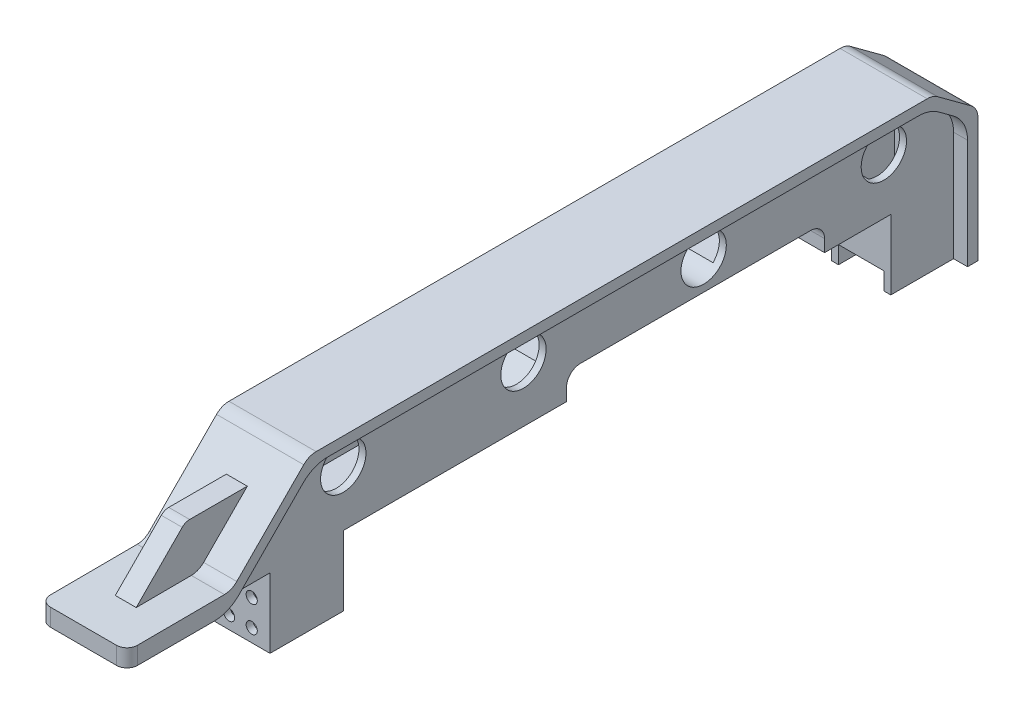
SolidWorks part; units mm, degrees
ref_plane "Front Plane" through (0, 0, 0) normal (0, 0, 1) x (1, 0, 0)
ref_plane "Top Plane" through (0, 0, 0) normal (0, 1, 0) x (1, 0, 0)
ref_plane "Right Plane" through (0, 0, 0) normal (1, 0, 0) x (0, 0, -1)
sketch "Sketch1" plane through (0, 0, 0) normal (1, 0, 0) x (0, 0, -1)
  line L0 (0, 0) -> (-130, 0)
  line L1 (0, 0) -> (74, 0) construction
  line L2 (0, 0) -> (0, 7.5)
  line L3 (0, 7.5) -> (74, 7.5)
  line L4 (74, 7.5) -> (74, 0)
  line L5 (74, 0) -> (114, 0)
  line L6 (-130, 0) -> (-130, 5)
  line L7 (-130, 5) -> (-100.0004, 5.1483)
  line L8 (-100.0004, 5.1483) -> (-77.8685, 27.5)
  line L9 (114, 0) -> (114, 18)
  line L10 (114, 18) -> (101.0882, 27.5)
  line L11 (101.0882, 27.5) -> (-77.8685, 27.5)
  dimension "D1" = 130
  dimension "D2" = 74
  dimension "D3" = 7.5
  dimension "D4" = 40
  dimension "D5" = 30
  dimension "D6" = 5
  dimension "D7" = 135
  dimension "D8" = 20
  dimension "D9" = 18
extrude "Boss-Extrude1" add sketch "Sketch1" along normal blind 25
sketch "Sketch4" plane through (25, 0, 0) normal (1, 0, 0) x (0, 0, -1)
  line L11 (-130, 0) -> (0, 0) construction
  line L12 (-130, 0) -> (0, 0) construction
  line L13 (-100.8762, 0) -> (0, 0)
  line L14 (0, 0) -> (111, 0)
  line L15 (74, 0) -> (114, 0) construction
  line L16 (111, 0) -> (111, 3)
  line L22 (-3, 3) -> (-3, 10.5)
  line L23 (-3, 10.5) -> (77, 10.5)
  line L24 (77, 10.5) -> (77, 3)
  line L25 (77, 3) -> (111, 3)
  line L26 (111, 3) -> (111, 16.4828)
  line L27 (111, 16.4828) -> (100.1035, 24.5)
  line L28 (100.1035, 24.5) -> (-76.6172, 24.5)
  line L29 (-76.6172, 24.5) -> (-97.9057, 3)
  line L30 (-97.9057, 3) -> (-3, 3)
  line L35 (111, 3) -> (111, 16.4828)
  line L36 (111, 16.4828) -> (100.1035, 24.5)
  line L37 (100.1035, 24.5) -> (-76.6172, 24.5)
  line L38 (-76.6172, 24.5) -> (-100.8762, 0)
  dimension "D1" = 3
extrude "Cut-Extrude1" cut sketch "Sketch4" against normal blind 4
ref_plane "Plane1" through (12.5, 0, 0) normal (1, 0, 0) x (0, 0, -1)
mirror "Mirror2" about plane through (12.5, 0, 0) normal (1, 0, 0) of "Cut-Extrude1"
fillet "Fillet1" radius 4 2 edges at (12.5, 7.5, -74) (12.5, 7.5, 0)
fillet "Fillet2" radius 10 8 edges at (23, 16.4828, -111) (23, 24.5, -100.1035) (2, 16.4828, -111) (2, 24.5, -100.1035) (2, 24.5, 76.6172) (23, 24.5, 76.6172) (2, 0, 100.8762) (23, 0, 100.8762)
fillet "Fillet3" radius 5 4 edges at (12.5, 18, -114) (12.5, 27.5, -101.0882) (12.5, 27.5, 77.8685) (12.5, 5.1483, 100.0004)
fillet "Fillet4" radius 3 2 edges at (0, 2.5, 130) (25, 2.5, 130)
sketch "Sketch5" plane through (12.5, 0, 0) normal (1, 0, 0) x (0, 0, -1)
  line L0 (-117.866, 5.06) -> (-103.7939, 19.2718)
  line L1 (-102.0714, 5.138) -> (-127, 5.0148) construction
  line L2 (-79.3359, 26.018) -> (-98.5432, 6.62) construction
  line L3 (-103.7939, 19.2718) -> (-72.6053, 19.2718)
  line L4 (-117.866, 5.06) -> (-95.866, 5.06)
  line L5 (-79.552, 21.536) -> (-97.9414, 2.964) construction
  line L6 (-72.6053, 19.2718) -> (-95.866, 5.06)
  dimension "D1" = 22
  dimension "D2" = 20
extrude "Boss-Extrude2" add sketch "Sketch5" along normal blind 3 and the other way blind 3
fillet "Fillet5" radius 3 1 edges at (12.5, 19.2718, 103.7939)
sketch "Sketch6" plane through (0, 0, 0) normal (0, -1, 0) x (1, 0, 0)
  line L1 (0, -111) -> (0, -114) construction
  line L2 (0, -111) -> (4, -111)
  line L3 (0, -111) -> (0, -114)
  line L4 (0, -114) -> (25, -114)
  line L5 (25, -111) -> (25, -114)
  line L6 (0, -111) -> (25, -114) construction
  line L7 (0, -114) -> (25, -111) construction
  line L8 (4, -111) -> (0, -111) construction
  line L9 (25, -114) -> (0, -114) construction
  line L10 (4, -74) -> (4, -111) construction
  line L11 (4, -111) -> (21, -111) construction
  line L12 (4, -111) -> (4, -93)
  line L13 (4, -93) -> (21, -93)
  line L14 (21, -111) -> (21, -93)
  line L15 (4, -111) -> (21, -93) construction
  line L16 (4, -93) -> (21, -111) construction
  line L17 (21, -74) -> (21, -111) construction
  line L18 (4, -111) -> (21, -111) construction
  line L19 (21, -111) -> (25, -111)
  line L21 (19, -95) -> (6, -95)
  line L22 (19, -95) -> (19, -109)
  line L23 (19, -109) -> (6, -109)
  line L24 (6, -95) -> (6, -109)
  line L25 (19, -95) -> (6, -109) construction
  line L26 (19, -109) -> (6, -95) construction
  point P6 (12.5, -112.5)
  point P16 (12.5, -102)
  point P21 (12.5, -102)
  dimension "D1" = 18
  dimension "D2" = 2
  dimension "D3" = 2
extrude "Boss-Extrude3" add sketch "Sketch6" along normal blind 20
sketch "Sketch7" plane through (0, -20, 0) normal (0, -1, 0) x (1, 0, 0)
  line L0 (19, -109) -> (19, -95) construction
  line L1 (19, -95) -> (6, -95)
  line L2 (19, -95) -> (19, -93)
  line L3 (19, -93) -> (6, -93)
  line L4 (6, -95) -> (6, -93)
  line L5 (19, -95) -> (6, -93) construction
  line L6 (19, -93) -> (6, -95) construction
  line L7 (19, -95) -> (6, -95) construction
  line L8 (21, -93) -> (4, -93) construction
  line L9 (6, -95) -> (6, -109) construction
  point P4 (12.5, -94)
sketch "Sketch8" plane through (0, 0, 0) normal (0, -1, 0) x (1, 0, 0)
  line L5 (21, 85) -> (21, 130) construction
  line L6 (21, 105.0473) -> (21, 0) construction
  line L8 (22, 130) -> (3, 130) construction
  line L9 (4, 105.0473) -> (4, 0) construction
  line L10 (21, 85) -> (4, 85)
  line L11 (21, 85) -> (21, 64)
  line L12 (21, 64) -> (19, 64)
  line L13 (4, 85) -> (4, 64)
  line L14 (21, 85) -> (4, 64) construction
  line L15 (21, 64) -> (4, 85) construction
  line L16 (19, 64) -> (6, 64) construction
  line L17 (6, 64) -> (19, 64) construction
  line L18 (6, 64) -> (6, 83)
  line L19 (6, 83) -> (19, 83)
  line L20 (19, 64) -> (19, 83)
  line L21 (6, 64) -> (19, 83) construction
  line L22 (6, 83) -> (19, 64) construction
  line L23 (6, 64) -> (4, 64)
  point P9 (12.5, 74.5)
  point P16 (12.5, 73.5)
  dimension "D1" = 45
  dimension "D2" = 21
  dimension "D3" = 2
  dimension "D4" = 2
  dimension "D5" = 2
extrude "Boss-Extrude4" add sketch "Sketch8" along normal blind 20
sketch "Sketch9" plane through (0, 0, 0) normal (0, -1, 0) x (1, 0, 0)
  line L0 (6, 64) -> (6, 83) construction
  line L1 (6, 64) -> (19, 64)
  line L2 (6, 64) -> (6, 66)
  line L3 (6, 66) -> (19, 66)
  line L4 (19, 64) -> (19, 66)
  line L5 (6, 64) -> (19, 66) construction
  line L6 (6, 66) -> (19, 64) construction
  line L7 (19, 83) -> (19, 64) construction
  point P4 (12.5, 65)
  dimension "D1" = 2
extrude "Boss-Extrude5" add sketch "Sketch9" along normal blind 8
extrude "Cut-Extrude2" cut sketch "Sketch7" against normal blind 5 contours L3 L4 L1 L2
sketch "Sketch11" plane through (0, 0, -114) normal (0, 0, -1) x (-1, 0, 0)
  line L0 (0, -20) -> (0, -12.5) construction
  line L1 (0, -20) -> (-25, -20) construction
  line L2 (0, -20) -> (0, 15.4713) construction
  line L3 (0, -16.25) -> (-25, -16.25) construction
  line L4 (-25, -20) -> (-25, 15.4713) construction
  line L5 (0, -16.25) -> (-9.25, -16.25) construction
  line L6 (-12.5, -20) -> (-12.5, -5) construction
  line L7 (0, -20) -> (0, -16.25)
  line L8 (-25, -20) -> (-25, -12.5) construction
  line L9 (-25, -12.5) -> (0, -12.5) construction
  circle A0 centre (-9.25, -16.25) radius 1.6
  circle A1 centre (-15.75, -16.25) radius 1.6
  circle A2 centre (-15.75, -8.75) radius 1.6
  circle A3 centre (-9.25, -8.75) radius 1.6
  circle A4 centre (-15.75, -16.25) radius 3 construction
  dimension "D2" = 3.2
  dimension "D5" = 6
  dimension "D1" = 9.25
  dimension "D3" = 3.75
  dimension "D4" = 7.5
extrude "Cut-Extrude3" cut sketch "Sketch11" against normal up to surface (19 mm away) contours A1 | A2 | A3 | A0 up to face at (12.5, -7.5, -95)
sketch "Sketch12" plane through (0, 0, 85) normal (0, 0, 1) x (1, 0, 0)
  line L0 (15.75, -8.75) -> (21, -8.75) construction
  line L1 (15.75, -8.75) -> (15.75, -5) construction
  line L3 (12.5, -20) -> (12.5, -5) construction
  line L6 (0, -12.5) -> (25, -12.5) construction
  line L7 (4, -20) -> (21, -20) construction
  line L8 (4, -20) -> (4, 0) construction
  line L9 (21, -20) -> (21, 0) construction
  circle A0 centre (15.75, -16.25) radius 1.6
  circle A1 centre (9.25, -16.25) radius 1.6
  circle A2 centre (9.25, -8.75) radius 1.6
  circle A3 centre (15.75, -8.75) radius 1.6
  circle A4 centre (9.25, -16.25) radius 3 construction
  dimension "D1" = 3.2
  dimension "D2" = 5.25
  dimension "D3" = 3.75
extrude "Cut-Extrude4" cut sketch "Sketch12" against normal up to surface (2 mm away) up to face at (12.5, -10, 83)
sketch "Sketch14" plane through (12.5, 0, 0) normal (1, 0, 0) x (0, 0, -1)
  line L0 (-83, 0) -> (-83, 13.4752)
  line L1 (-66, 0) -> (-66, 4)
  line L2 (-66, 4) -> (-13.3251, 4)
  line L3 (-13.3251, 4) -> (-5.8251, 11.5)
  line L4 (-5.8251, 11.5) -> (87.0794, 11.5)
  line L5 (95, 0) -> (95, 3.5794)
  line L6 (95, 3.5794) -> (87.0794, 11.5)
  line L7 (109, 0) -> (109, 10.0924)
  line L8 (109, -20) -> (109, 0) construction
  line L9 (95, 0) -> (109, 0) construction
  line L10 (109, 10.0924) -> (95.5924, 23.5)
  line L15 (-72.9752, 23.5) -> (-83, 13.4752)
  line L16 (-83, 0) -> (-66, 0)
  line L17 (95, 0) -> (109, 0)
  line L18 (95.5924, 23.5) -> (-72.9752, 23.5)
  line L19 (-64, 0) -> (0, 0) construction
  line L20 (99.447, 27.5) -> (-75.783, 27.5) construction
  line L21 (70, 7.5) -> (4, 7.5) construction
  dimension "D1" = 135
  dimension "D2" = 135
  dimension "D3" = 135
  dimension "D4" = 135
  dimension "D5" = 4
  dimension "D6" = 4
  dimension "D7" = 4
extrude "Cut-Extrude5" cut sketch "Sketch14" against normal blind 6.5 and the other way blind 6.5
sketch "Sketch15" plane through (4, 0, 0) normal (-1, 0, 0) x (0, 0, 1)
  line L0 (-37, 7.5) -> (-37, 24.5) construction
  line L1 (-70, 7.5) -> (-4, 7.5) construction
  line L2 (-96.8211, 24.5) -> (72.4461, 24.5) construction
  line L3 (-37, 16) -> (-111, 16) construction
  line L4 (-37, 16) -> (84, 16) construction
  line L6 (-111, 16) -> (-13.5, 16) construction
  line L7 (-13.5, 16) -> (-13.5, 7.5) construction
  line L8 (-111, 16) -> (-91, 16) construction
  circle A1 centre (-91, 16) radius 6.5
  circle A2 centre (-39.3333, 16) radius 6.5
  circle A3 centre (64, 16) radius 6.5
  circle A4 centre (12.3333, 16) radius 6.5
  dimension "D5" = 13
  dimension "D1" = 74
  dimension "D2" = 121
  dimension "D3" = 97.5
  dimension "D4" = 20
  dimension "D6" = 51.6667
extrude "Cut-Extrude6" cut sketch "Sketch15" against normal up to surface (17 mm away)
